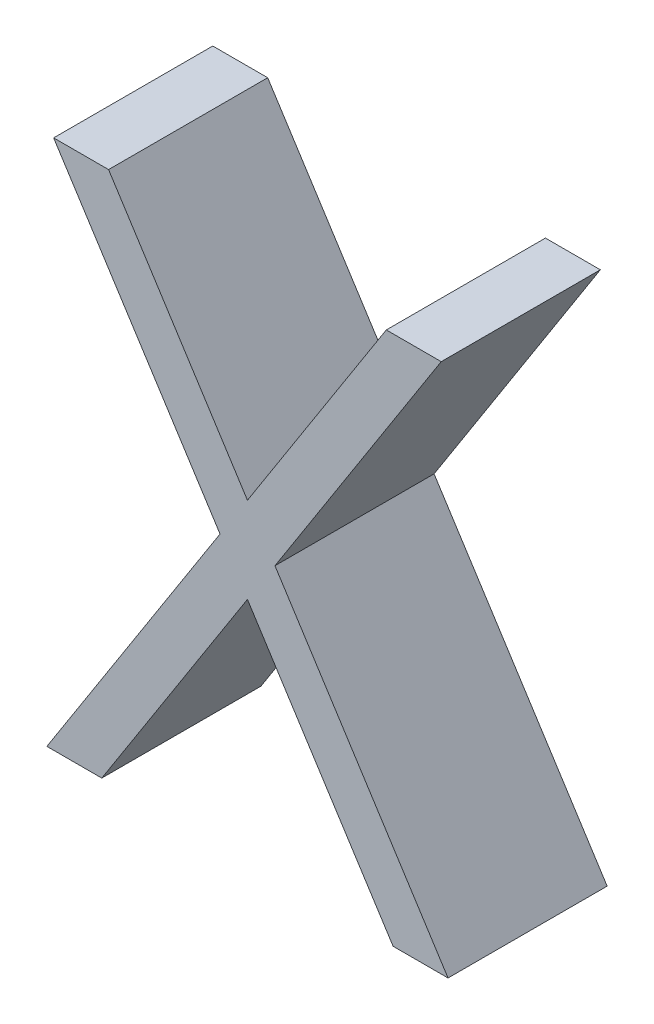
SolidWorks part; units mm, degrees
ref_plane "Plan de face" through (0, 0, 0) normal (0, 0, 1) x (1, 0, 0)
ref_plane "Plan de dessus" through (0, 0, 0) normal (0, 1, 0) x (1, 0, 0)
ref_plane "Plan de droite" through (0, 0, 0) normal (1, 0, 0) x (0, 0, -1)
sketch "Esquisse1" plane through (0, 0, 0) normal (0, 0, 1) x (1, 0, 0)
  text T0 "X" font "Century Gothic" height 5
extrude "Boss.-Extru.1" add sketch "Esquisse1" along normal blind 1.5
